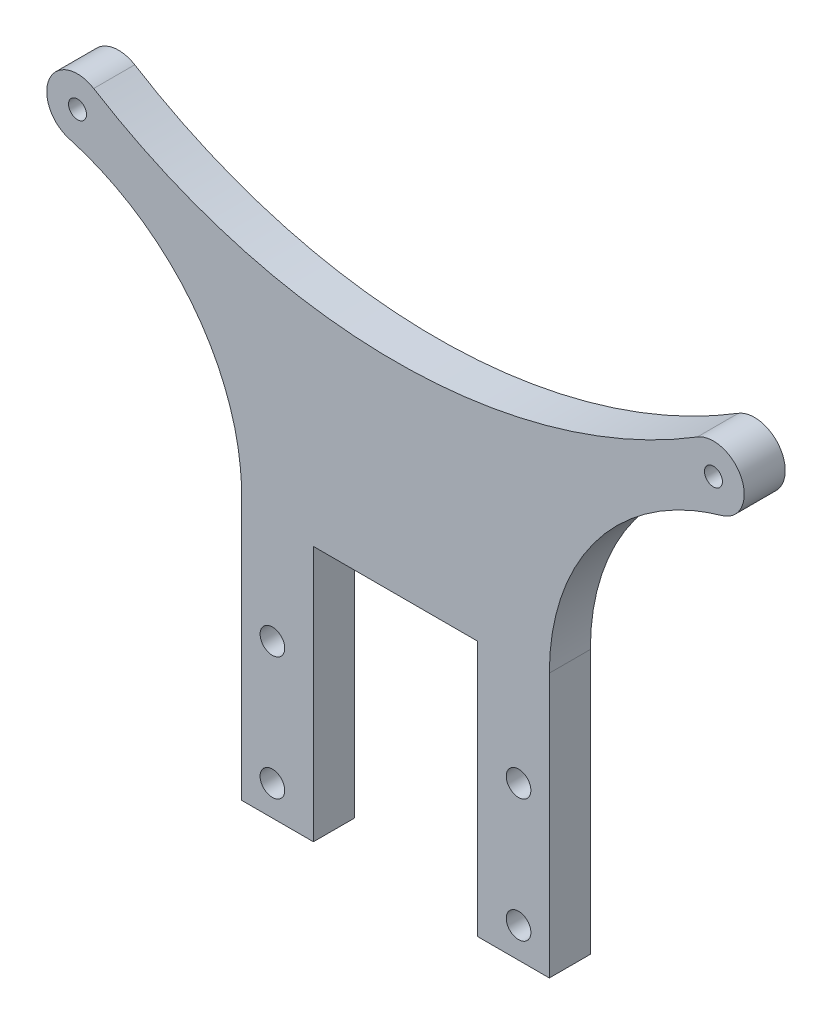
SolidWorks part; units mm, degrees
ref_plane "Front Plane" through (0, 0, 0) normal (0, 0, 1) x (1, 0, 0)
ref_plane "Top Plane" through (0, 0, 0) normal (0, 1, 0) x (1, 0, 0)
ref_plane "Right Plane" through (0, 0, 0) normal (1, 0, 0) x (0, 0, -1)
sketch "Sketch1" plane through (0, 0, 0) normal (0, 0, 1) x (1, 0, 0)
  line L0 (0, 45.085) -> (0, -57.25) construction
  line L1 (12.7, 0) -> (-12.7, 0)
  line L2 (-12.7, 0) -> (-12.7, -39.5939)
  line L4 (-49.2125, 45.085) -> (6.4719, 45.085) construction
  line L5 (-23.8125, -39.5939) -> (-23.8125, 1.27)
  line L6 (12.7, 0) -> (12.7, -39.5939)
  line L7 (-23.8125, -39.5939) -> (-12.7, -39.5939)
  line L8 (23.8125, -5.08) -> (23.8125, 1.27)
  line L9 (23.8125, -39.5939) -> (23.8125, -5.08)
  line L11 (23.8125, -39.5939) -> (12.7, -39.5939)
  circle A0 centre (-19.05, -15.875) radius 1.905
  arc A1 (-46.7103, 44.3747) -> (-50.503, 35.7382) centre (-49.2125, 40.3225) ccw
  arc A2 (46.7103, 44.3747) -> (-46.7103, 44.3747) centre (0, 120.0186) cw
  circle A3 centre (19.05, -15.875) radius 1.905
  circle A4 centre (-49.2125, 40.3225) radius 1.3891
  circle A5 centre (-19.05, -34.925) radius 1.905
  circle A6 centre (19.05, -34.925) radius 1.905
  circle A9 centre (49.2125, 40.3225) radius 1.3891
  arc A10 (46.7103, 44.3747) -> (50.503, 35.7382) centre (49.2125, 40.3225) cw
  ellipse E0 centre (-60.8178, 1.27) end of major axis (-23.8125, 1.27) minor radius 35.8906 (-50.503, 35.7382) -> (-23.8125, 1.27) cw
  ellipse E1 centre (60.8178, 1.27) end of major axis (97.8232, 1.27) minor radius 35.8906 (50.503, 35.7382) -> (23.8125, 1.27) ccw
  point P9 (-49.2125, 40.3225)
  point P14 (0, 31.115)
  point P28 (0, 0)
  dimension "D4" = 19.05
  dimension "D7" = 9.525
  dimension "D9" = 50.503
  dimension "D12" = 2.7781
  dimension "D13" = 3.81
  dimension "D14" = 15.875
  dimension "D5" = 88.9036
  dimension "D3" = 19.05
  dimension "D1" = 12.7
  dimension "D8" = 13.97
  dimension "D10" = 1.27
  dimension "D11" = 60.8178
  dimension "D21" = 5.08
extrude "Boss-Extrude1" add sketch "Sketch1" along normal blind 6.35
